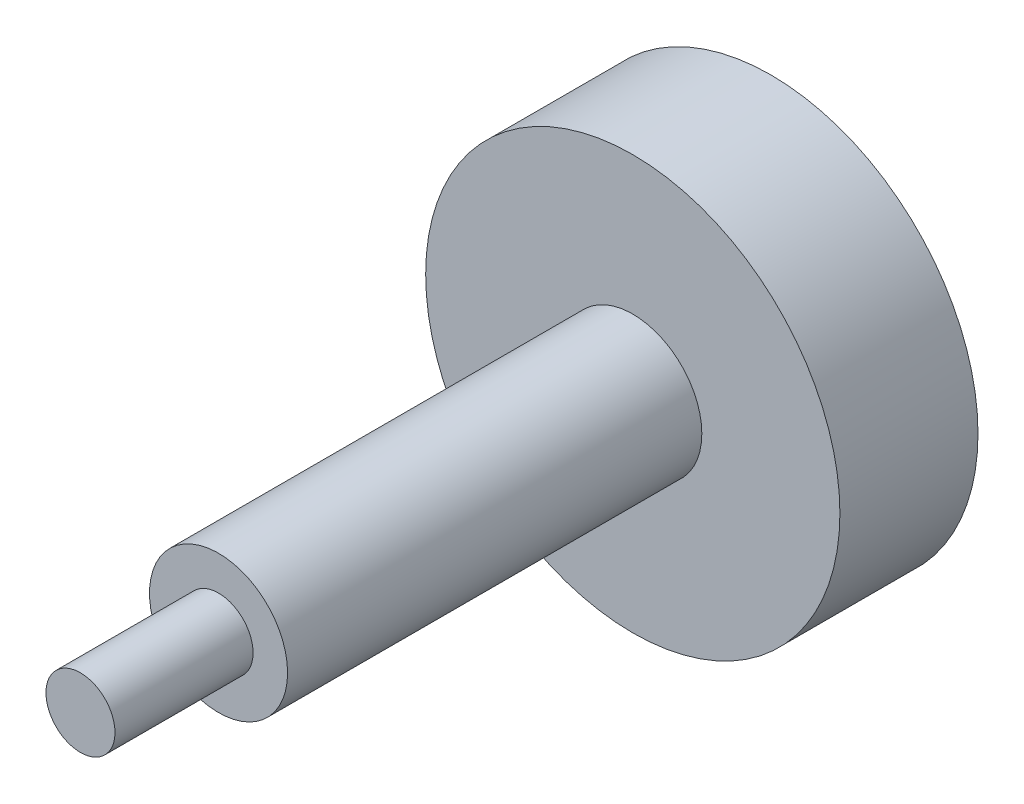
SolidWorks part; units mm, degrees
ref_plane "Front Plane" through (0, 0, 0) normal (0, 0, 1) x (1, 0, 0)
ref_plane "Top Plane" through (0, 0, 0) normal (0, 1, 0) x (1, 0, 0)
ref_plane "Right Plane" through (0, 0, 0) normal (1, 0, 0) x (0, 0, -1)
sketch "Sketch1" plane through (0, 0, 0) normal (0, 0, 1) x (1, 0, 0)
  circle A0 centre (0, 0) radius 300
  dimension "D1" = 600
extrude "Boss-Extrude1" add sketch "Sketch1" along normal blind 200
sketch "Sketch2" plane through (0, 0, 200) normal (0, 0, 1) x (1, 0, 0)
  circle A0 centre (0, 0) radius 100
  dimension "D1" = 200
extrude "Boss-Extrude2" add sketch "Sketch2" along normal blind 600
sketch "Sketch3" plane through (0, 0, 800) normal (0, 0, 1) x (1, 0, 0)
  circle A0 centre (0, 0) radius 50
  dimension "D1" = 100
extrude "Boss-Extrude3" add sketch "Sketch3" along normal blind 200
